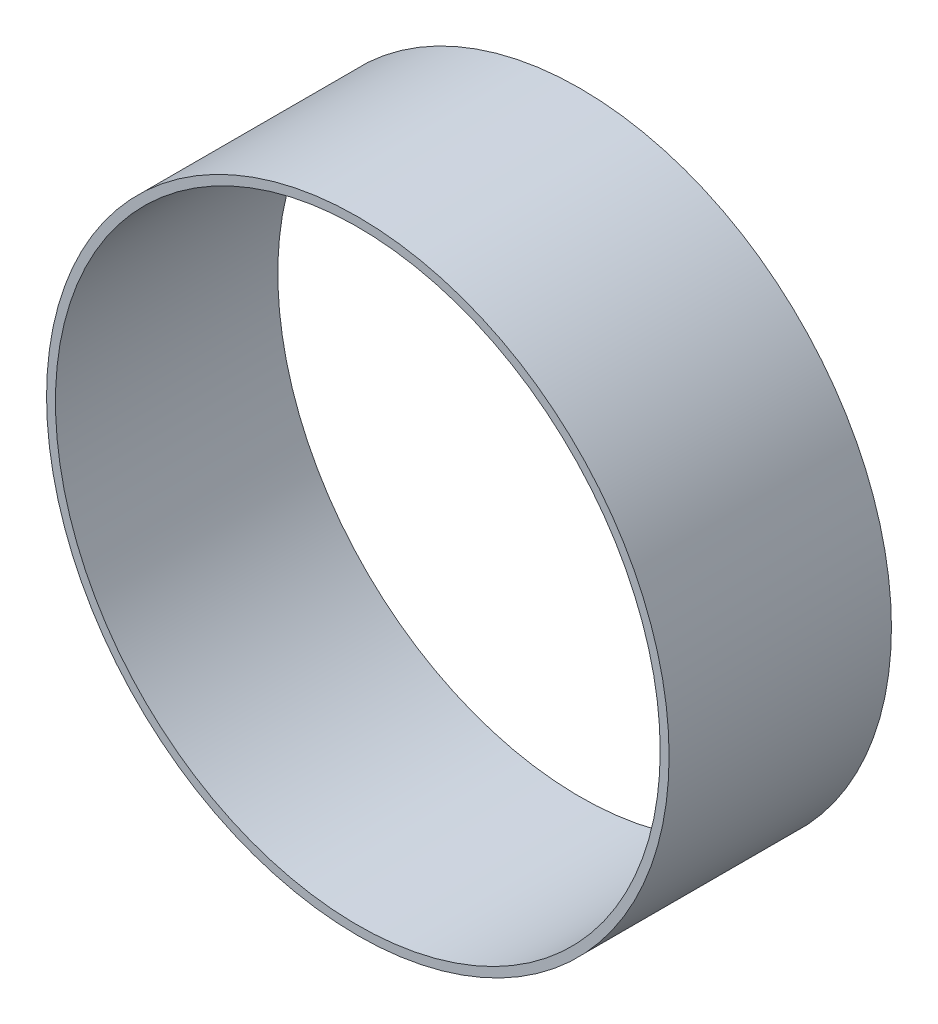
SolidWorks part; units mm, degrees
material "Литая легированная сталь"
ref_plane "Спереди" through (0, 0, 0) normal (0, 0, 1) x (1, 0, 0)
ref_plane "Сверху" through (0, 0, 0) normal (0, 1, 0) x (1, 0, 0)
ref_plane "Справа" through (0, 0, 0) normal (1, 0, 0) x (0, 0, -1)
sketch "Эскиз1" plane through (0, 0, 0) normal (1, 0, 0) x (0, 0, -1)
  line L0 (0, 0) -> (50, 0) construction
  line L1 (50, 0) -> (50, 68) construction
  line L2 (50, 68) -> (0, 68) construction
  line L3 (0, 68) -> (0, 0) construction
  line L4 (0, 68) -> (0, 70)
  line L5 (0, 70) -> (50, 70)
  line L6 (50, 70) -> (50, 68)
  line L7 (50, 68) -> (0, 68)
  dimension "D1" = 136
  dimension "D2" = 140
  dimension "D3" = 50
revolve "Повернуть1" add sketch "Эскиз1" angle 360 about L0
